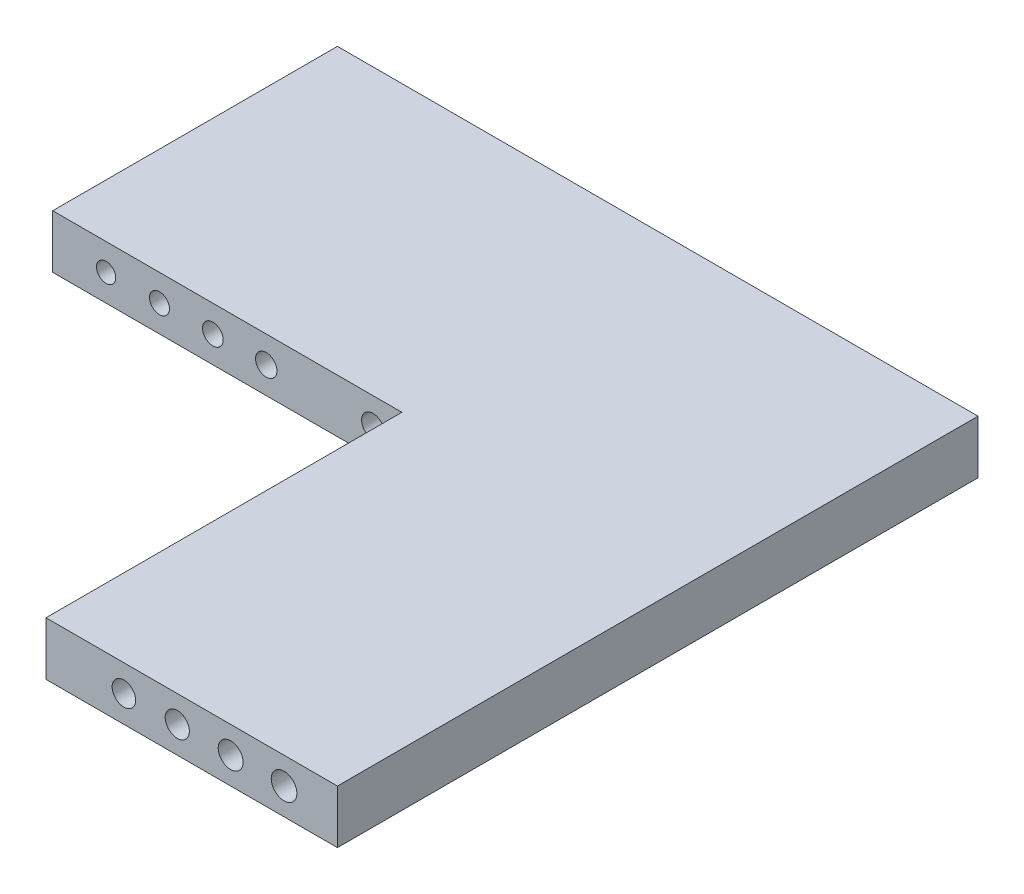
SolidWorks part; units mm, degrees
ref_plane "Front Plane" through (0, 0, 0) normal (0, 0, 1) x (1, 0, 0)
ref_plane "Top Plane" through (0, 0, 0) normal (0, 1, 0) x (1, 0, 0)
ref_plane "Right Plane" through (0, 0, 0) normal (1, 0, 0) x (0, 0, -1)
sketch "Sketch1" plane through (0, 0, 0) normal (0, 0, 1) x (1, 0, 0)
  line L0 (-40, 0) -> (49960, 0) construction
  line L1 (-45, -3.75) -> (45, -3.75)
  line L2 (-45, -3.75) -> (-45, 3.75)
  line L3 (-45, 3.75) -> (45, 3.75)
  line L4 (45, -3.75) -> (45, 3.75)
  line L5 (-45, -3.75) -> (45, 3.75) construction
  line L6 (-45, 3.75) -> (45, -3.75) construction
  circle A1 centre (-37.5, 0) radius 1.35
  circle A2 centre (-30, 0) radius 1.4
  circle A3 centre (-22.5, 0) radius 1.45
  circle A4 centre (-15, 0) radius 1.5
  circle A6 centre (0, 0) radius 1.6
  circle A8 centre (15, 0) radius 1.65
  circle A9 centre (22.5, 0) radius 1.7
  circle A10 centre (37.5, 0) radius 1.8
  circle A11 centre (30, 0) radius 1.75
  point P0 (0, 0)
  point P8 (-45, 0)
  point P9 (45, 0)
  point P10 (0, 0)
  point P11 (-7.5, 0)
  point P13 (7.5, 0)
  point P14 (15, 0)
  point P15 (22.5, 0)
  point P16 (30, 0)
  point P17 (37.5, 0)
  point P18 (-15, 0)
  point P19 (-22.5, 0)
  point P20 (-30, 0)
  point P21 (-37.5, 0)
  dimension "D3" = 6
  dimension "D5" = 2.7
  dimension "D6" = 2.8
  dimension "D7" = 2.9
  dimension "D8" = 3.2
  dimension "D9" = 3
  dimension "D10" = 3.6
  dimension "D11" = 3.5
  dimension "D12" = 3.4
  dimension "D13" = 3.3
  dimension "D1" = 7.5
  dimension "D2" = 90
  dimension "D4" = 6
extrude "Boss-Extrude1" add sketch "Sketch1" along normal blind 90
sketch "Sketch2" plane through (0, 0, 90) normal (0, 0, 1) x (1, 0, 0)
  line L0 (4.0558, 3.75) -> (4.0558, -3.75)
  line L4 (45, -3.75) -> (45, 3.75)
  line L5 (45, 3.75) -> (-45, 3.75)
  line L6 (-45, 3.75) -> (-45, -3.75)
  line L7 (-45, -3.75) -> (45, -3.75)
  line L9 (4.0558, 3.75) -> (-45, 3.75)
  line L10 (-45, 3.75) -> (-45, -3.75)
  line L11 (-45, -3.75) -> (4.0558, -3.75)
  dimension "D1" = 0
extrude "Cut-Extrude1" cut sketch "Sketch2" against normal blind 50
